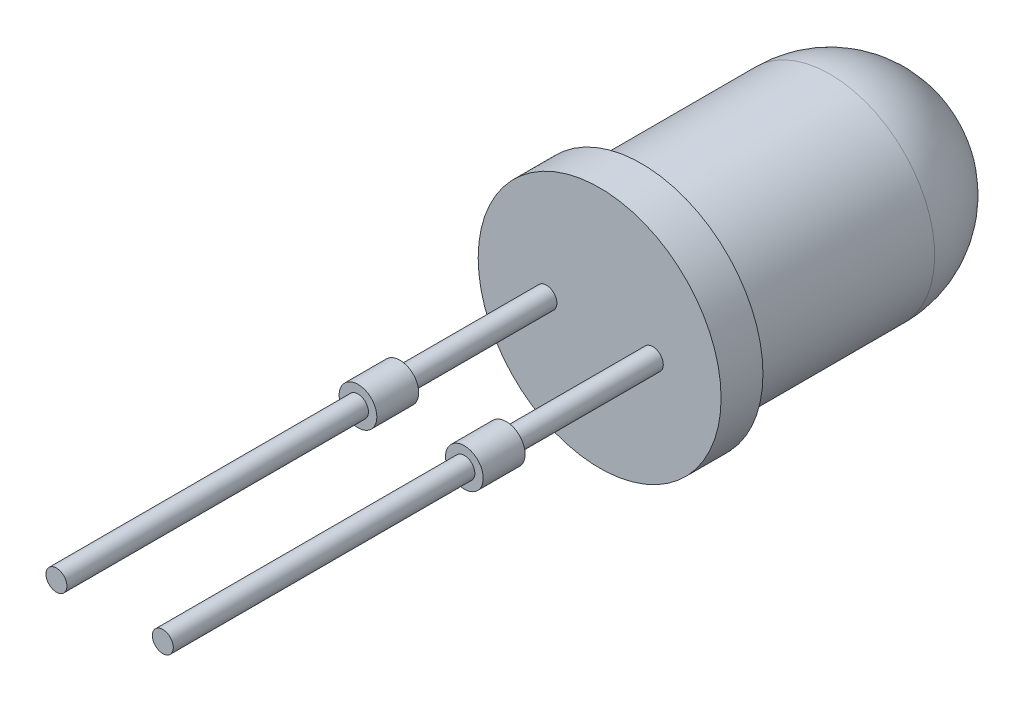
SolidWorks part; units mm, degrees
ref_plane "前视基准面" through (0, 0, 0) normal (0, 0, 1) x (1, 0, 0)
ref_plane "上视基准面" through (0, 0, 0) normal (0, 1, 0) x (1, 0, 0)
ref_plane "右视基准面" through (0, 0, 0) normal (1, 0, 0) x (0, 0, -1)
sketch "草图1" plane through (0, 0, 0) normal (0, 0, 1) x (1, 0, 0)
  circle A0 centre (0, 0) radius 2.5
  dimension "D1" = 5
extrude "拉伸1" add sketch "草图1" along normal blind 5.5
sketch "草图2" plane through (0, 0, 5.5) normal (0, 0, 1) x (1, 0, 0)
  circle A0 centre (0, 0) radius 2.9
  dimension "D1" = 5.8
extrude "拉伸2" add sketch "草图2" against normal blind 1
sketch "草图3" plane through (0, 0, 4.5) normal (0, 0, -1) x (-1, 0, 0)
  line L0 (0, 2.011) -> (0, -2.1052) construction
  line L1 (-2.1813, 0) -> (2.3335, 0) construction
  circle A0 centre (-1.27, 0) radius 0.25
  circle A1 centre (1.27, 0) radius 0.25
  dimension "D1" = 0.5
  dimension "D2" = 2.54
extrude "拉伸3" add sketch "草图3" against normal blind 12.7
sketch "草图5" plane through (0, 0, 0) normal (1, 0, 0) x (0, 0, -1)
  line L0 (0, 2.5) -> (0, 0)
  line L1 (2.5, 0) -> (0, 0)
  arc A0 (0, 2.5) -> (2.5, 0) centre (0, 0) cw
  dimension "D1" = 2.5
revolve "旋转2" add sketch "草图5" angle 360 about L1
sketch "草图6" plane through (0, 0, 5.5) normal (0, 0, 1) x (1, 0, 0)
  circle A0 centre (-1.27, 0) radius 0.25 construction
  circle A1 centre (1.27, 0) radius 0.25 construction
  circle A12 centre (-1.27, 0) radius 0.25
  circle A13 centre (1.27, 0) radius 0.25
  circle A14 centre (-1.27, 0) radius 0.45
  circle A15 centre (1.27, 0) radius 0.45
  dimension "D1" = 0.2
extrude "凸台-拉伸1" add sketch "草图6" along normal blind 4.5
sketch "草图7" plane through (0, 0, 5.5) normal (0, 0, 1) x (1, 0, 0)
  circle A0 centre (-1.27, 0) radius 0.45 construction
  circle A1 centre (-1.27, 0) radius 0.25 construction
  circle A2 centre (1.27, 0) radius 0.25 construction
  circle A3 centre (1.27, 0) radius 0.45 construction
  circle A4 centre (-1.27, 0) radius 0.45
  circle A5 centre (-1.27, 0) radius 0.25
  circle A6 centre (1.27, 0) radius 0.25
  circle A7 centre (1.27, 0) radius 0.45
extrude "切除-拉伸2" cut sketch "草图7" along normal blind 3.5
